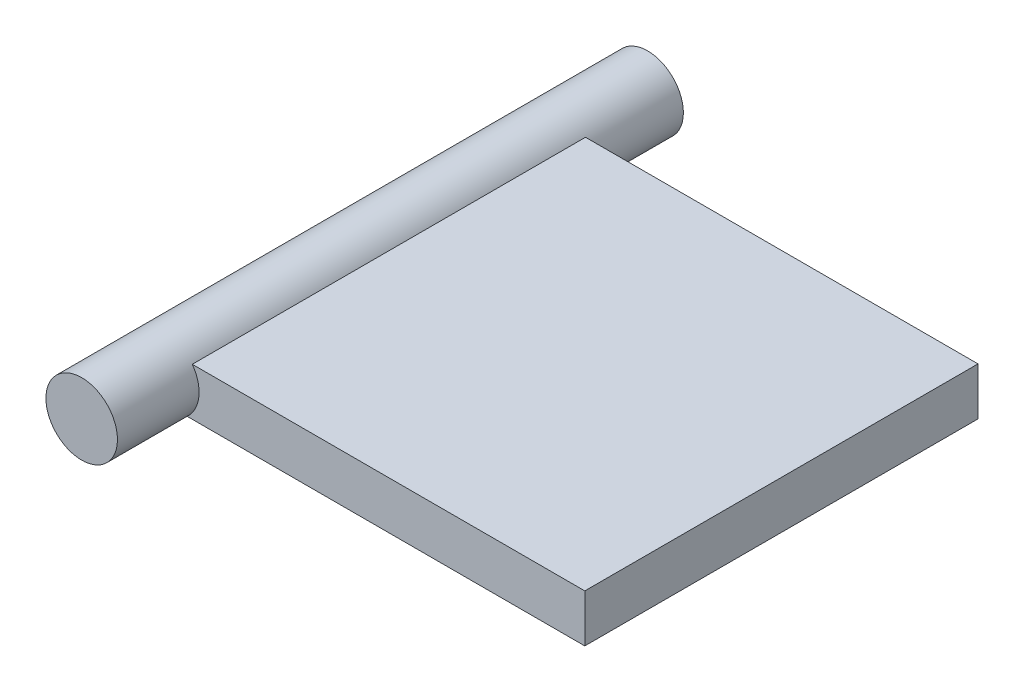
SolidWorks part; units mm, degrees
ref_plane "Front Plane" through (0, 0, 0) normal (0, 0, 1) x (1, 0, 0)
ref_plane "Top Plane" through (0, 0, 0) normal (0, 1, 0) x (1, 0, 0)
ref_plane "Right Plane" through (0, 0, 0) normal (1, 0, 0) x (0, 0, -1)
sketch "Sketch1" plane through (0, 0, 0) normal (0, 0, 1) x (1, 0, 0)
  circle A0 centre (0, 0) radius 75
  dimension "D1" = 150
extrude "Boss-Extrude1" add sketch "Sketch1" along normal blind 1187
ref_plane "Plane1" through (10, 0, 0) normal (1, 0, 0) x (0, 0, -1)
sketch "Sketch3" plane through (10, 0, 0) normal (1, 0, 0) x (0, 0, -1)
  line L1 (-1015.7778, 43.9583) -> (-191.066, 43.9583)
  line L2 (-1015.7778, 43.9583) -> (-1015.7778, -56.0417)
  line L3 (-1015.7778, -56.0417) -> (-191.066, -56.0417)
  line L4 (-191.066, 43.9583) -> (-191.066, -56.0417)
  dimension "D1" = 100
extrude "Boss-Extrude2" add sketch "Sketch3" along normal blind 874
